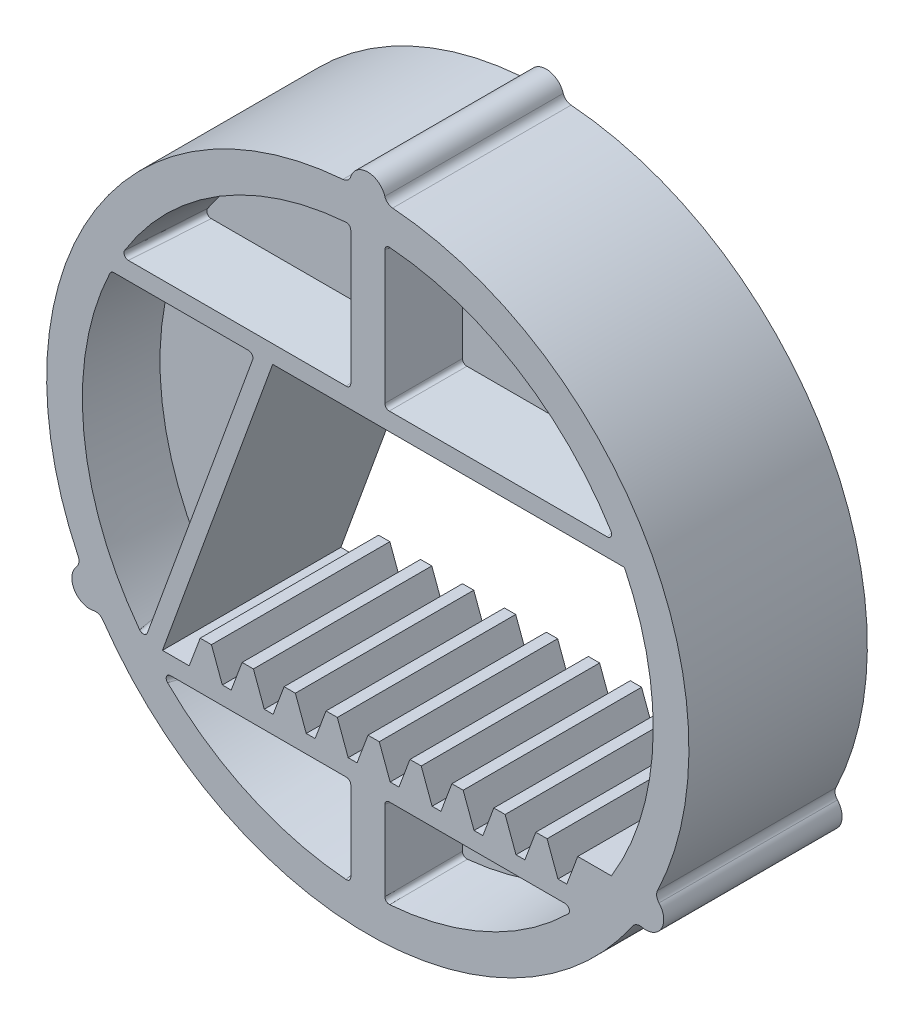
SolidWorks part; units mm, degrees
ref_plane "Plan de face" through (0, 0, 0) normal (0, 0, 1) x (1, 0, 0)
ref_plane "Plan de dessus" through (0, 0, 0) normal (0, 1, 0) x (1, 0, 0)
ref_plane "Plan de droite" through (0, 0, 0) normal (1, 0, 0) x (0, 0, -1)
sketch "Esquisse1" plane through (0, 0, 0) normal (0, 0, 1) x (1, 0, 0)
  line L0 (14.3875, 7) -> (-5.3312, 7)
  line L1 (-5.3312, 7) -> (-11.5097, -9.9753)
  line L2 (-11.5097, -9.9753) -> (-10.0097, -9.9753)
  line L3 (-7.6582, -9.977) -> (-8.1539, -9.977)
  line L4 (-8.1539, -9.977) -> (-8.7634, -8.3253)
  line L5 (-8.7634, -8.3253) -> (-9.3955, -8.3253)
  line L6 (-9.3955, -8.3253) -> (-10.0097, -9.9753)
  line L7 (-5.3067, -9.9787) -> (-5.8023, -9.9787)
  line L8 (-5.8023, -9.9787) -> (-6.4119, -8.327)
  line L9 (-6.4119, -8.327) -> (-7.044, -8.327)
  line L10 (-7.044, -8.327) -> (-7.6582, -9.977)
  line L11 (-2.9552, -9.9805) -> (-3.4508, -9.9805)
  line L12 (-3.4508, -9.9805) -> (-4.0603, -8.3287)
  line L13 (-4.0603, -8.3287) -> (-4.6925, -8.3287)
  line L14 (-4.6925, -8.3287) -> (-5.3067, -9.9787)
  line L15 (-0.6036, -9.9822) -> (-1.0993, -9.9822)
  line L16 (-1.0993, -9.9822) -> (-1.7088, -8.3305)
  line L17 (-1.7088, -8.3305) -> (-2.341, -8.3305)
  line L18 (-2.341, -8.3305) -> (-2.9552, -9.9805)
  line L19 (1.7479, -9.9839) -> (1.2522, -9.9839)
  line L20 (1.2522, -9.9839) -> (0.6427, -8.3322)
  line L21 (0.6427, -8.3322) -> (0.0106, -8.3322)
  line L22 (0.0106, -8.3322) -> (-0.6036, -9.9822)
  line L23 (4.0994, -9.9857) -> (3.6038, -9.9857)
  line L24 (3.6038, -9.9857) -> (2.9942, -8.3339)
  line L25 (2.9942, -8.3339) -> (2.3621, -8.3339)
  line L26 (2.3621, -8.3339) -> (1.7479, -9.9839)
  line L27 (6.451, -9.9874) -> (5.9553, -9.9874)
  line L28 (5.9553, -9.9874) -> (5.3458, -8.3357)
  line L29 (5.3458, -8.3357) -> (4.7136, -8.3357)
  line L30 (4.7136, -8.3357) -> (4.0994, -9.9857)
  line L31 (8.8025, -9.9891) -> (8.3068, -9.9891)
  line L32 (8.3068, -9.9891) -> (7.6973, -8.3374)
  line L33 (7.6973, -8.3374) -> (7.0652, -8.3374)
  line L34 (7.0652, -8.3374) -> (6.451, -9.9874)
  line L35 (11.154, -9.9909) -> (10.6584, -9.9909)
  line L36 (10.6584, -9.9909) -> (10.0488, -8.3391)
  line L37 (10.0488, -8.3391) -> (9.4167, -8.3391)
  line L38 (9.4167, -8.3391) -> (8.8025, -9.9891)
  line L39 (0, -4.95) -> (0, 4.95) construction
  line L41 (13.6539, -8.3409) -> (11.7682, -8.3409)
  line L42 (11.7682, -8.3409) -> (11.154, -9.9909)
  arc A0 (-14.8447, -10.1801) -> (14.8447, -10.1801) centre (0, 0) ccw
  circle A1 centre (0, 0) radius 16
  arc A2 (-16.3226, -8.321) -> (-15.3675, -9.9753) centre (-15.5885, -9) ccw
  arc A3 (-16.3226, -8.321) -> (-16.2386, -7.7658) centre (-16.6897, -7.9815) ccw
  arc A4 (-15.3675, -9.9753) -> (-14.8447, -10.1801) centre (-15.257, -10.4629) cw
  arc A5 (0.9551, 18.2963) -> (-0.9551, 18.2963) centre (0, 18) ccw
  arc A6 (0.9551, 18.2963) -> (1.3939, 17.9459) centre (1.4326, 18.4444) ccw
  arc A7 (-0.9551, 18.2963) -> (-1.3939, 17.9459) centre (-1.4326, 18.4444) cw
  arc A8 (15.3675, -9.9753) -> (14.8447, -10.1801) centre (15.257, -10.4629) ccw
  arc A9 (16.3226, -8.321) -> (16.2386, -7.7658) centre (16.6897, -7.9815) cw
  arc A10 (16.3226, -8.321) -> (15.3675, -9.9753) centre (15.5885, -9) cw
  arc A11 (16.2386, -7.7658) -> (1.3939, 17.9459) centre (0, 0) ccw
  arc A12 (-1.3939, 17.9459) -> (-16.2386, -7.7658) centre (0, 0) ccw
  point P5 (-16.4545, -9.5)
  point P17 (0, 17)
  point P61 (0, 18)
  point P101 (16.4545, -9.5)
  point P102 (-12.5097, -9.9753)
  dimension "D1" = 36
  dimension "D7" = 2
  dimension "D56" = 0.5
  dimension "D58" = 0.5
  dimension "D2" = 1.6517
  dimension "D3" = 0.6321
  dimension "D4" = 1.65
  dimension "D5" = 0.4957
  dimension "D6" = 0.6142
  dimension "D8" = 0.6321
  dimension "D9" = 1.65
  dimension "D10" = 0.4957
  dimension "D11" = 0.6142
  dimension "D12" = 1.6517
  dimension "D13" = 0.6321
  dimension "D14" = 1.65
  dimension "D15" = 0.4957
  dimension "D16" = 0.6142
  dimension "D17" = 1.6517
  dimension "D18" = 0.6321
  dimension "D19" = 1.65
  dimension "D20" = 0.4957
  dimension "D21" = 0.6142
  dimension "D22" = 1.6517
  dimension "D23" = 0.6321
  dimension "D24" = 1.65
  dimension "D25" = 0.4957
  dimension "D26" = 0.6142
  dimension "D27" = 1.6517
  dimension "D28" = 0.6321
  dimension "D29" = 1.65
  dimension "D30" = 0.4957
  dimension "D31" = 0.6142
  dimension "D32" = 1.6517
  dimension "D33" = 0.6321
  dimension "D34" = 1.65
  dimension "D35" = 0.4957
  dimension "D36" = 0.6142
  dimension "D37" = 1.6517
  dimension "D38" = 0.6321
  dimension "D39" = 1.65
  dimension "D40" = 0.4957
  dimension "D41" = 0.6142
  dimension "D42" = 1.6517
  dimension "D43" = 0.6321
  dimension "D44" = 1.65
  dimension "D45" = 0.4957
  dimension "D46" = 0.6142
  dimension "D47" = 1.6517
  dimension "D48" = 11
  dimension "D49" = 1.65
  dimension "D50" = 1.5
  dimension "D51" = 0.6142
  dimension "D52" = 110
  dimension "D53" = 120
  dimension "D54" = 1
  dimension "D55" = 1
  dimension "D57" = 1
extrude "Boss.-Extru.1" add sketch "Esquisse1" along normal mid plane 10 contours L0 A1 L41 L42 L35 L36 L37 L38 L31 L32 L33 L34 L27 L28 L29 L30 L23 L24 L25 L26 L19 L20 L21 L22 L15 L16 L17 L18 L11 L12 L13 L14 L7 L8 L9 L10 L3 L4 L5 L6 L2 L1 | A7 A12 A3 A2 A4 A0 A8 A10 A9 A11 A6 A5 A1 L42
sketch "Esquisse2" plane through (0, 0, 5) normal (0, 0, 1) x (1, 0, 0)
  line L0 (-6.3312, 7) -> (-14.3875, 7)
  line L1 (-6.3312, 7) -> (-12.5097, -9.9753)
  line L2 (-0.9551, 15.9715) -> (-0.9551, 8)
  line L3 (-0.9551, 8) -> (-13.8564, 8)
  line L4 (0.9551, 15.9715) -> (0.9551, 8)
  line L5 (0.9551, 8) -> (13.8564, 8)
  line L6 (-11.6423, -10.9753) -> (-0.9551, -10.9753)
  line L7 (-0.9551, -10.9753) -> (-0.9551, -15.9715)
  line L8 (0.9551, -15.9715) -> (0.9551, -10.9753)
  line L9 (0.9551, -10.9753) -> (11.6423, -10.9753)
  line L10 (-11.5097, -9.9753) -> (-10.0097, -9.9753) construction
  line L11 (14.3875, 7) -> (-5.3312, 7) construction
  arc A0 (-14.3875, 7) -> (-12.5097, -9.9753) centre (0, 0) ccw
  arc A1 (-11.6423, -10.9753) -> (-0.9551, -15.9715) centre (0, 0) ccw
  arc A2 (0.9551, -15.9715) -> (11.6423, -10.9753) centre (0, 0) ccw
  arc A3 (-0.9551, 15.9715) -> (-13.8564, 8) centre (0, 0) ccw
  arc A4 (0.9551, 15.9715) -> (13.8564, 8) centre (0, 0) cw
  circle A5 centre (0, 0) radius 16 construction
  dimension "D1" = 1
  dimension "D2" = 1
  dimension "D3" = 1
extrude "Enlèv. mat.-Extru.1" cut sketch "Esquisse2" against normal blind 4 draft 5
fillet "Congé1" radius 0.25 15 edges at (1.1301, -11.1503, 3) (-1.1301, -11.1503, 3) (-6.5811, 6.825, 3) (-1.1301, 8.175, 3) (1.1301, 8.175, 3)
mirror "Symétrie1" about plane through (0, 0, 0) normal (0, 0, 1) of "Congé1", "Enlèv. mat.-Extru.1"
